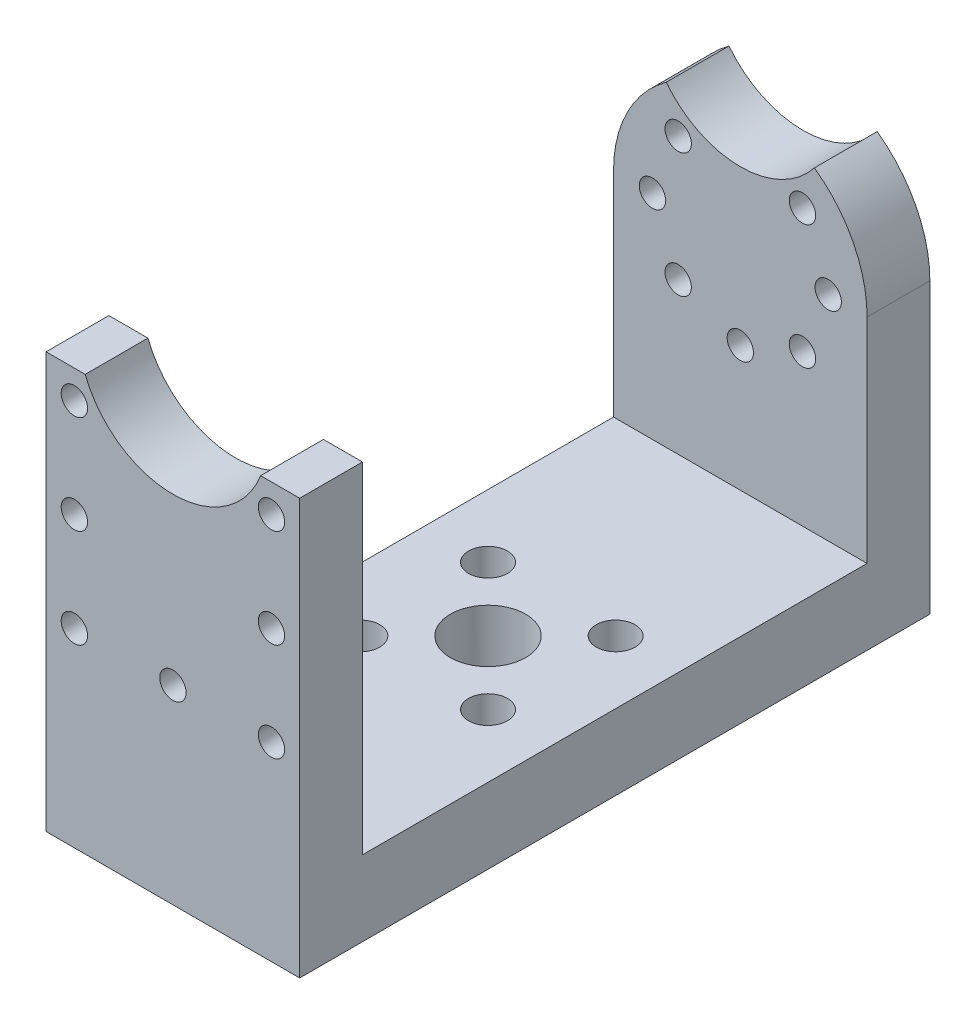
SolidWorks part; units mm, degrees
ref_plane "Front Plane" through (0, 0, 0) normal (0, 0, 1) x (1, 0, 0)
ref_plane "Top Plane" through (0, 0, 0) normal (0, 1, 0) x (1, 0, 0)
ref_plane "Right Plane" through (0, 0, 0) normal (1, 0, 0) x (0, 0, -1)
sketch "Sketch1" plane through (0, 0, 0) normal (0, 0, 1) x (1, 0, 0)
  line L0 (0, 0) -> (0, -20) construction
  line L1 (-10.1, 0) -> (-10.1, -20)
  line L2 (10.1, 0) -> (10.1, -20)
  line L3 (-10.1, -20) -> (10.1, -20)
  arc A0 (10.1, 0) -> (-10.1, 0) centre (0, 0) ccw
  dimension "D1" = 20.2
  dimension "D2" = 20
extrude "Boss-Extrude1" add sketch "Sketch1" along normal blind 50.2
sketch "Sketch2" plane through (-10.1, 0, 0) normal (-1, 0, 0) x (0, 0, 1)
  line L0 (50.2, -10) -> (45.2, -10) construction
  line L1 (50.2, 0) -> (50.2, -20) construction
  line L2 (0, -10) -> (5, -10) construction
  line L3 (0, 0) -> (0, -20) construction
  line L4 (25.1, -20) -> (25.1, -17) construction
  line L5 (50.2, -20) -> (0, -20) construction
  line L6 (5, -10) -> (5, -17)
  line L7 (5, -17) -> (45.2, -17)
  line L8 (45.2, -17) -> (45.2, -10)
  line L9 (45.2, -10) -> (45.2, 11.8668)
  line L10 (45.2, 11.8668) -> (5, 11.8668)
  line L11 (5, 11.8668) -> (5, -10)
  dimension "D1" = 5
  dimension "D2" = 5
  dimension "D3" = 3
extrude "Cut-Extrude2" cut sketch "Sketch2" against normal blind 44.2
sketch "Sketch3" plane through (0, 0, 50.2) normal (0, 0, 1) x (1, 0, 0)
  line L0 (0, 10.1) -> (-10.1, 10.1) construction
  line L1 (-10.1, 10.1) -> (-10.1, 0) construction
  line L2 (0, 10.1) -> (10.1, 10.1) construction
  line L3 (10.1, 10.1) -> (10.1, 0) construction
  line L4 (-10.1, 0) -> (-10.1, 10.1)
  line L5 (-10.1, 10.1) -> (10.1, 10.1)
  line L6 (10.1, 10.1) -> (10.1, 0)
  line L7 (10.1, 0) -> (-10.1, 0)
  arc A0 (10.1, 0) -> (-10.1, 0) centre (0, 0) ccw construction
extrude "Boss-Extrude2" add sketch "Sketch3" against normal blind 5
sketch "Sketch4" plane through (0, 0, 50.2) normal (0, 0, 1) x (1, 0, 0)
  line L0 (0, 0) -> (-10.1, 0) construction
  line L1 (-10.1, 10.1) -> (-10.1, -20) construction
  line L2 (-10.1, 0) -> (10.1, 0) construction
  line L3 (-10.1, 10.1) -> (-10.1, -9.9) construction
  line L4 (-10.1, -9.9) -> (10.1, -9.9) construction
  line L5 (10.1, -20) -> (10.1, 10.1) construction
  line L6 (10.1, -9.9) -> (10.1, 10.1) construction
  line L7 (10.1, 10.1) -> (-10.1, 10.1) construction
  line L8 (0, 10.1) -> (0, -9.9) construction
  line L9 (10.1, -9.9) -> (10.1, 10.1) construction
  line L10 (10.1, 10.1) -> (-10.1, -9.9) construction
  line L11 (-6.8, 7.85) -> (6.8, 7.85) construction
  line L12 (-6.8, -7.85) -> (6.8, -7.85) construction
  circle A2 centre (-7.85, 7.85) radius 1.05
  circle A3 centre (7.85, 7.85) radius 1.05
  circle A4 centre (-7.85, -7.85) radius 1.05
  circle A5 centre (7.85, -7.85) radius 1.05
  circle A6 centre (0, 7.85) radius 1.05
  circle A7 centre (0, -7.85) radius 1.05
  circle A8 centre (-7.85, 0) radius 1.05
  circle A9 centre (7.85, 0) radius 1.05
  dimension "D1" = 2.1
  dimension "D2" = 20
  dimension "D4" = 2.25
  dimension "D5" = 2.1
  dimension "D6" = 2.1
  dimension "D7" = 2.1
  dimension "D8" = 2.1
  dimension "D9" = 2.25
  dimension "D10" = 2.25
  dimension "D3" = 2.25
extrude "Cut-Extrude3" cut sketch "Sketch4" against normal mid plane 22
sketch "Sketch5" plane through (0, 0, 50.2) normal (0, 0, 1) x (1, 0, 0)
  line L0 (0, -4) -> (0, 20.32) construction
  circle A0 centre (0, 0) radius 4
  circle A1 centre (0, 12.82) radius 7.5
  dimension "D1" = 8
  dimension "D2" = 15
  dimension "D3" = 24.32
extrude "Cut-Extrude4" cut sketch "Sketch5" against normal mid plane 22
sketch "Sketch6" plane through (0, 0, 50.2) normal (0, 0, 1) x (1, 0, 0)
  circle A0 centre (0, 0) radius 4
  dimension "D1" = 8
extrude "Boss-Extrude3" add sketch "Sketch6" against normal blind 5
sketch "Sketch7" plane through (0, 0, 0) normal (0, 0, -1) x (-1, 0, 0)
  line L0 (0, 4) -> (0, 6) construction
  line L1 (0, 6) -> (0, 7) construction
  circle A0 centre (0, 0) radius 4
  circle A1 centre (0, 7) radius 1.05
  circle A2 centre (-4.9497, 4.9497) radius 1.05
  circle A3 centre (-7, 0) radius 1.05
  circle A4 centre (-4.9497, -4.9497) radius 1.05
  circle A5 centre (0, -7) radius 1.05
  circle A6 centre (4.9497, -4.9497) radius 1.05
  circle A7 centre (7, 0) radius 1.05
  circle A8 centre (4.9497, 4.9497) radius 1.05
  point P24 (0, 0)
  dimension "D1" = 8
  dimension "D4" = 2.1
  dimension "D2" = 2
  dimension "D3" = 1
  dimension "D5" = 8
extrude "Cut-Extrude5" cut sketch "Sketch7" against normal mid plane 32
sketch "Sketch8" plane through (0, 0, 0) normal (0, 0, -1) x (-1, 0, 0)
  line L0 (0, 20.32) -> (0, -4) construction
  circle A1 centre (0, 12.82) radius 7.5
  circle A2 centre (0, 0) radius 4 construction
  dimension "D1" = 15
  dimension "D2" = 24.32
extrude "Cut-Extrude6" cut sketch "Sketch8" against normal mid plane 22
sketch "Sketch9" plane through (0, 0, 0) normal (0, 0, -1) x (-1, 0, 0)
  circle A0 centre (0, 0) radius 4
  dimension "D1" = 8
extrude "Boss-Extrude4" add sketch "Sketch9" against normal blind 5
ref_plane "Plane1" through (0, -20, 0) normal (0, -1, 0) x (-1, 0, 0)
sketch "Sketch11" plane through (0, -20, 0) normal (0, -1, 0) x (-1, 0, 0)
  line L1 (-10.1, 0) -> (10.1, 0)
  line L2 (-10.1, 0) -> (-10.1, -50.2)
  line L3 (-10.1, -50.2) -> (10.1, -50.2)
  line L4 (10.1, 0) -> (10.1, -50.2)
extrude "Boss-Extrude5" add sketch "Sketch11" along normal blind 3
ref_plane "Plane2" through (0, -17, 0) normal (0, 1, 0) x (1, 0, 0)
sketch "Sketch12" plane through (0, -17, 0) normal (0, 1, 0) x (1, 0, 0)
  line L0 (-10.1, -25.1) -> (10.1, -25.1) construction
  line L1 (-10.1, -5) -> (-10.1, -45.2) construction
  line L2 (10.1, -5) -> (10.1, -45.2) construction
  line L3 (0, -5) -> (0, -45.2) construction
  line L4 (10.1, -5) -> (-10.1, -5) construction
  line L5 (10.1, -45.2) -> (-10.1, -45.2) construction
  line L6 (0, -25.1) -> (-5.0841, -20.0159) construction
  line L7 (-5.0841, -20.0159) -> (-5.0841, -25.1) construction
  circle A0 centre (0, -25.1) radius 3
  circle A1 centre (-5.0841, -20.0159) radius 1.55
  circle A5 centre (5.0841, -20.0159) radius 1.55
  circle A6 centre (5.0841, -30.1841) radius 1.55
  circle A7 centre (-5.0841, -30.1841) radius 1.55
  point P25 (-0.3874, -24.4228)
  point P26 (0, -25.1)
  dimension "D1" = 6
  dimension "D2" = 3.1
  dimension "D3" = 90
  dimension "D4" = 45
  dimension "D6" = 4
  dimension "D5" = 7.19
extrude "Cut-Extrude8" cut sketch "Sketch12" against normal blind 23
